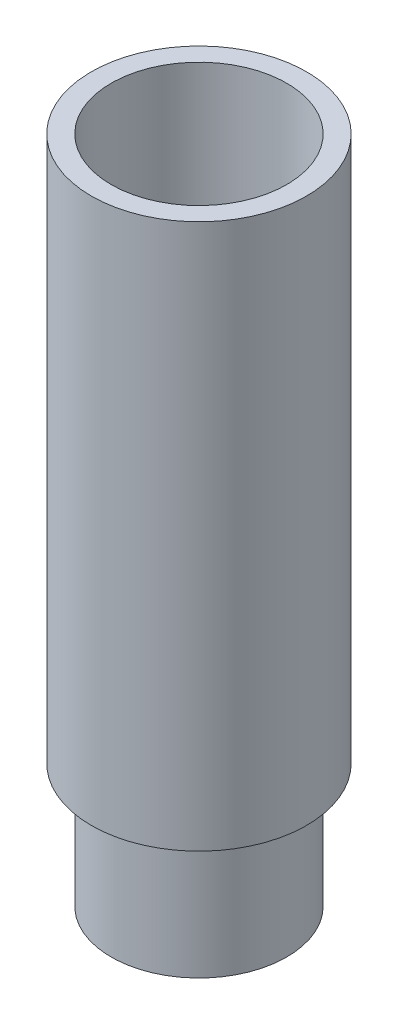
SolidWorks part; units mm, degrees
ref_plane "Front Plane" through (0, 0, 0) normal (0, 0, 1) x (1, 0, 0)
ref_plane "Top Plane" through (0, 0, 0) normal (0, 1, 0) x (1, 0, 0)
ref_plane "Right Plane" through (0, 0, 0) normal (1, 0, 0) x (0, 0, -1)
sketch "Sketch1" plane through (0, 0, 0) normal (0, 1, 0) x (1, 0, 0)
  circle A0 centre (0, 0) radius 9.0043
  circle A1 centre (0, 0) radius 6.9723
  dimension "D1" = 18.0086
  dimension "D2" = 2.032
extrude "Boss-Extrude1" add sketch "Sketch1" along normal blind 19.05
sketch "Sketch2" plane through (0, 19.05, 0) normal (0, 1, 0) x (1, 0, 0)
  circle A0 centre (0, 0) radius 9.0043 construction
  circle A1 centre (0, 0) radius 9.0043
  circle A2 centre (0, 0) radius 11.0363
  dimension "D1" = 2.032
extrude "Boss-Extrude2" add sketch "Sketch2" along normal blind 49.53 and the other way blind 6.35
sketch "Sketch3" plane through (0, 0, 0) normal (0, 0, 1) x (1, 0, 0)
  line L1 (0, 0) -> (2.54, 0)
  line L2 (0, 0) -> (0, 2.54)
  line L3 (0, 2.54) -> (2.54, 2.54)
  line L4 (2.54, 0) -> (2.54, 2.54)
  dimension "D1" = 2.54
extrude "Boss-Extrude3" add sketch "Sketch3" along normal up to surface and the other way up to surface up to face at (0, 19.05, 6.9723) other way up to face at (0, 19.05, 6.9723)
